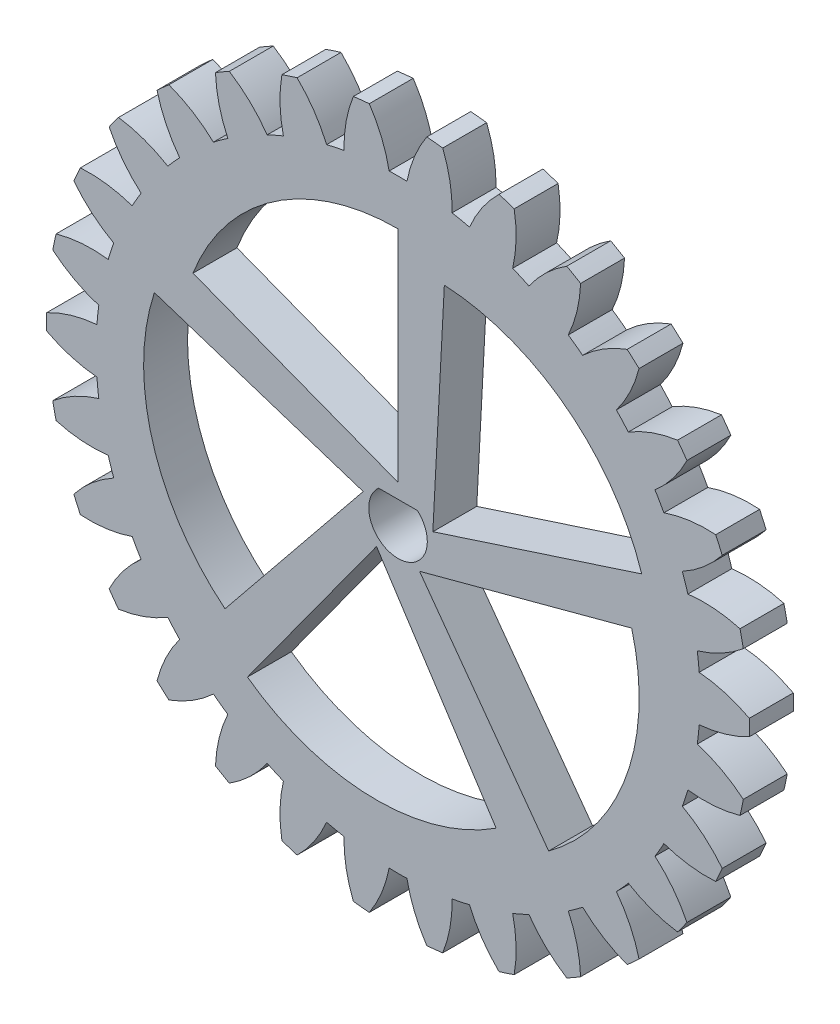
SolidWorks part; units mm, degrees
ref_plane "Front Plane" through (0, 0, 0) normal (0, 0, 1) x (1, 0, 0)
ref_plane "Top Plane" through (0, 0, 0) normal (0, 1, 0) x (1, 0, 0)
ref_plane "Right Plane" through (0, 0, 0) normal (1, 0, 0) x (0, 0, -1)
sketch "Sketch1" plane through (0, 0, 0) normal (0, 0, 1) x (1, 0, 0)
  circle A0 centre (0, 0) radius 24
  dimension "addendumDiameter" = 48
extrude "Boss-Extrude1" add sketch "Sketch1" along normal blind 3
sketch "Sketch2" plane through (0, 0, 0) normal (0, 0, -1) x (-1, 0, 0)
  line L0 (0, 0) -> (0, 35.9116) construction
  line L1 (0, 0) -> (-2.6805, 25.5029) construction
  line L2 (-1.177, 22.4692) -> (-2.3487, 22.346) construction
  circle A0 centre (0, 0) radius 20.625 construction
  circle A1 centre (0, 0) radius 21.1431 construction
  circle A2 centre (0, 0) radius 22.5 construction
  arc A3 (0.6079, 20.616) -> (-0.6079, 20.616) centre (0, 0) ccw
  arc A4 (1.965, 23.9194) -> (-1.965, 23.9194) centre (0, 0) ccw
  circle A5 centre (0, 0) radius 24 construction
  arc A6 (-1.965, 23.9194) -> (-0.6079, 20.616) centre (-9.4458, 18.9158) cw
  arc A7 (1.965, 23.9194) -> (0.6079, 20.616) centre (9.4458, 18.9158) ccw
  dimension "basediameter" = 42.2862
  dimension "pitchDiameter" = 45
  dimension "D1" = 41.25
  dimension "D3" = 9
  dimension "D2" = 6
  dimension "D4" = 1.1781
extrude "Cut-Extrude2" cut sketch "Sketch2" against normal blind 5 contours A7 A3 A6 A4
pattern_circular "CirPattern1" count 30 over 360 about axis through (0, 0, 0) along (0, 0, 1) of "Cut-Extrude2"
sketch "Sketch3" plane through (0, 0, 0) normal (0, 0, -1) x (-1, 0, 0)
  line L2 (14.0037, 7.8755) -> (0, 2.5)
  line L3 (0, 2.5) -> (0, 17.5)
  arc A1 (14.0037, 7.8755) -> (0, 17.5) centre (0, 2.5) ccw
  dimension "D2" = 69
  dimension "D1" = 15
  dimension "D3" = 2.5
extrude "Cut-Extrude4" cut sketch "Sketch3" against normal blind 10 contours L2 L3 A1
pattern_circular "CirPattern3" count 5 over 360 about axis through (0, 0, 0) along (0, 0, 1) of "Cut-Extrude4"
sketch "Sketch4" plane through (0, 0, 3) normal (0, 0, 1) x (1, 0, 0)
  line L0 (-1.3229, 1.5) -> (1.3229, 1.5)
  arc A0 (-1.3229, 1.5) -> (1.3229, 1.5) centre (0, 0) ccw
  dimension "D1" = 1.5
  dimension "D2" = 2
extrude "Cut-Extrude5" cut sketch "Sketch4" against normal blind 8
equation "\"module\"= 1.5"
equation "\"teeth\"= 30"
equation "\"pressureAngle\"= 20deg"
equation "\"gearThickness\"= 3"
equation "\"addendumFactor\"= 1"
equation "\"dedendumFactor\"= 1.25"
equation "\"pitch\"= 1 / \"module\""
equation "\"pitchDiameter\"= \"teeth\" / \"pitch\""
equation "\"addendum\"= \"addendumFactor\" / \"pitch\""
equation "\"dedendum\"= \"dedendumFactor\" / \"pitch\""
equation "\"D1@Sketch2\"=\"pitchDiameter\" - 2 * \"dedendum\" "
equation "\"basediameter@Sketch2\"=\"pitchDiameter\" * cos ( \"pressureAngle\" )"
equation "\"pitchDiameter@Sketch2\"=\"pitchDiameter\""
equation "\"D2@Sketch2\"=180/\"teeth\""
equation "\"D3@Sketch2\"=\"pitchDiameter\"/5"
equation "\"D1@CirPattern1\"=\"teeth\""
equation "\"addendumDiameter@Sketch1\"=\"pitchDiameter\"+2*\"addendum\""
equation "\"D1@Boss-Extrude1\"=\"gearThickness\""
equation "\"D4@Sketch2\"=PI/2/\"pitch\"/2"
